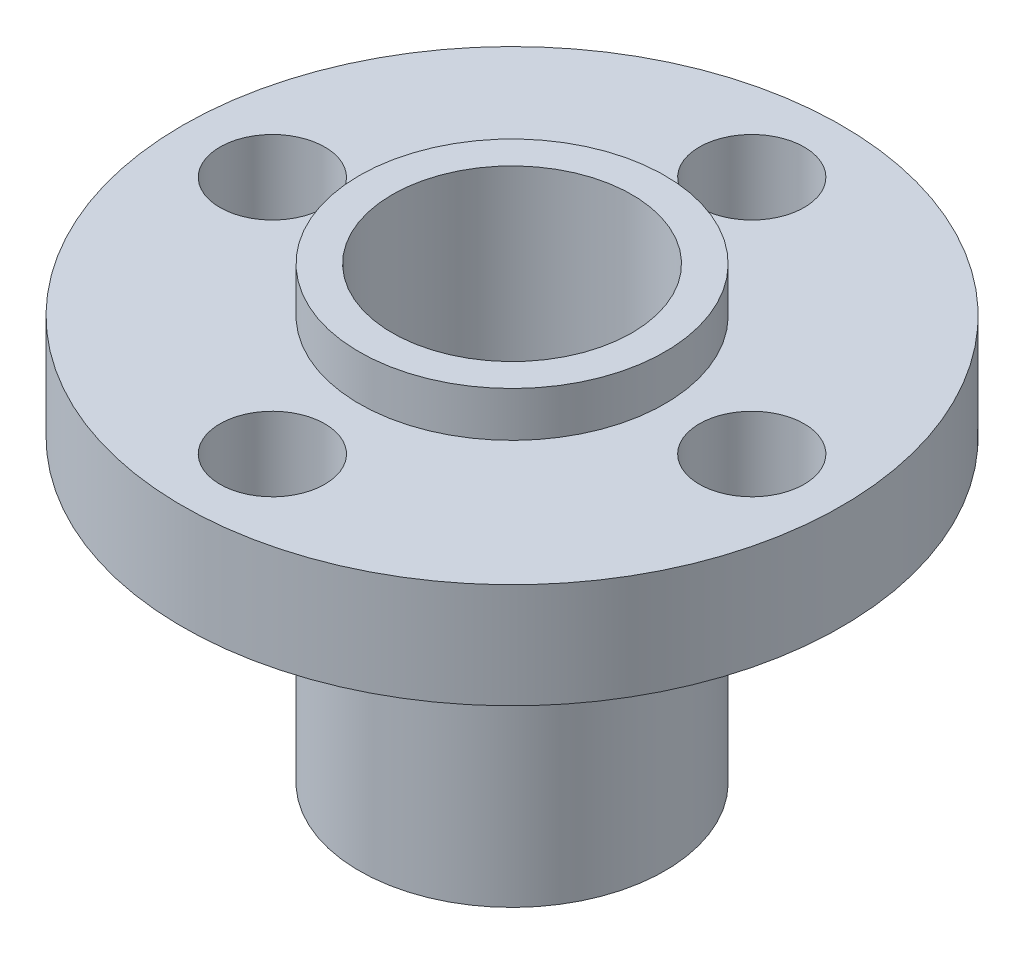
SolidWorks part; units mm, degrees
material "Aço carbono fundido"
ref_plane "Plano frontal" through (0, 0, 0) normal (0, 0, 1) x (1, 0, 0)
ref_plane "Plano superior" through (0, 0, 0) normal (0, 1, 0) x (1, 0, 0)
ref_plane "Plano direito" through (0, 0, 0) normal (1, 0, 0) x (0, 0, -1)
sketch "Esboço1" plane through (0, 0, 0) normal (0, 0, 1) x (1, 0, 0)
  line L0 (0, 0) -> (-5.1, 0)
  line L1 (-5.1, 0) -> (-5.1, 10)
  line L2 (-5.1, 10) -> (-11, 10)
  line L3 (-11, 10) -> (-11, 13.5)
  line L4 (-11, 13.5) -> (-5.1, 13.5)
  line L5 (0, 13.5) -> (0, 0)
  line L6 (-5.1, 13.5) -> (-5.1, 15)
  line L7 (-5.1, 15) -> (0, 15)
  line L8 (0, 15) -> (0, 13.5)
  dimension "D1" = 5.1
  dimension "D2" = 11
  dimension "D3" = 10
  dimension "D4" = 1.5
  dimension "D5" = 3.5
revolve "Revolução1" add sketch "Esboço1" angle 360 about L5
sketch "Esboço2" plane through (0, 0, 0) normal (0, -1, 0) x (1, 0, 0)
  circle A0 centre (0, 0) radius 4
  dimension "D1" = 8
extrude "Corte-extrusão1" cut sketch "Esboço2" against normal blind 57
sketch "Esboço3" plane through (0, 13.5, 0) normal (0, 1, 0) x (1, 0, 0)
  line L0 (0, 0) -> (0, 11) construction
  circle A2 centre (0, 0) radius 11 construction
  circle A4 centre (0, 8) radius 1.75
  dimension "D1" = 3.5
  dimension "D2" = 8
extrude "Corte-extrusão2" cut sketch "Esboço3" against normal through all
pattern_circular "PadrãoCircular1" count 4 over 360 about axis through (0, 0, 0) along (0, 1, 0) of "Corte-extrusão2"
